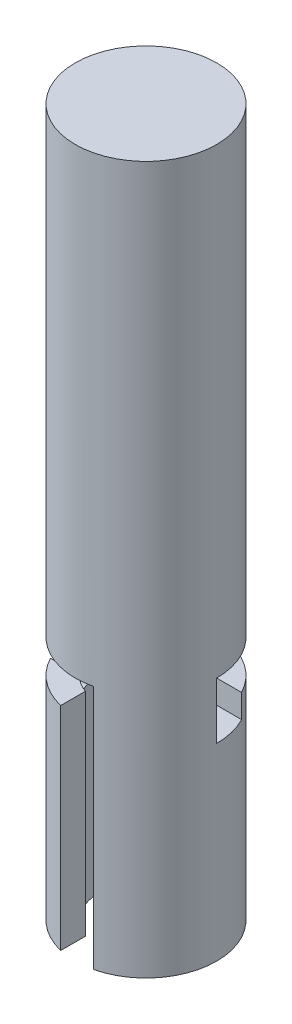
SolidWorks part; units mm, degrees
ref_plane "Front Plane" through (0, 0, 0) normal (0, 0, 1) x (1, 0, 0)
ref_plane "Top Plane" through (0, 0, 0) normal (0, 1, 0) x (1, 0, 0)
ref_plane "Right Plane" through (0, 0, 0) normal (1, 0, 0) x (0, 0, -1)
sketch "Sketch1" plane through (0, 0, 0) normal (0, 1, 0) x (1, 0, 0)
  circle A0 centre (0, 0) radius 15
  dimension "D1" = 30
extrude "Boss-Extrude1" add sketch "Sketch1" along normal mid plane 150
sketch "Sketch2" plane through (0, -75, 0) normal (0, -1, 0) x (1, 0, 0)
  line L0 (0, 15) -> (0, -15) construction
  line L1 (3.5, 15) -> (3.5, -15)
  line L2 (-3.5, 15) -> (-3.5, -15)
  circle A0 centre (0, 0) radius 15 construction
  arc A1 (3.5, 15) -> (-3.5, 15) centre (0, 15) ccw
  arc A2 (-3.5, -15) -> (3.5, -15) centre (0, -15) ccw
  point P6 (0, 0)
  dimension "D1" = 3.5
extrude "Cut-Extrude1" cut sketch "Sketch2" against normal blind 52
ref_plane "Plane1" through (0, -26.5, 0) normal (0, 1, 0) x (1, 0, 0)
sketch "Sketch3" plane through (0, -26.5, 0) normal (0, 1, 0) x (1, 0, 0)
  line L1 (-14.9801, 0) -> (-15.3281, -9.9939)
  line L2 (0, -7) -> (-0.348, -16.9939)
  line L3 (15, 0) -> (0, 7)
  line L4 (15, 0) -> (15.348, 9.9939)
  line L5 (0, 7) -> (0.348, 16.9939)
  line L6 (15.348, 9.9939) -> (0.348, 16.9939)
  line L7 (-15.3281, -9.9939) -> (-0.348, -16.9939)
  line L8 (-14.9801, 0) -> (0, -7)
  circle A0 centre (0, 0) radius 15 construction
  point P0 (0, -7)
  point P5 (-14.9801, 0)
  dimension "D1" = 7
  dimension "D2" = 7
  dimension "D3" = 10
extrude "Cut-Extrude2" cut sketch "Sketch3" against normal mid plane 7
ref_plane "Plane2" through (0, -35, 0) normal (0, 1, 0) x (1, 0, 0)
sketch "Sketch9" plane through (0, -75, 0) normal (0, -1, 0) x (1, 0, 0)
  circle A0 centre (0, 0) radius 10
  dimension "D1" = 20
extrude "Cut-Extrude12" cut sketch "Sketch9" against normal blind 70
ref_plane "Plane5" through (15, 0, 0) normal (1, 0, 0) x (0, 0, -1)
sketch "Sketch17" plane through (15, 0, 0) normal (1, 0, 0) x (0, 0, -1)
  line L0 (0, -23) -> (0, -35)
  line L1 (0, -23) -> (7, -23)
  line L2 (0, -35) -> (7, -35)
  line L3 (7, -23) -> (7, -35)
  line L4 (16.5, -35) -> (-16.5, -35) construction
  dimension "D1" = 7
extrude "Cut-Extrude19" cut sketch "Sketch17" against normal blind 15
ref_plane "Plane6" through (-15, 0, 0) normal (1, 0, 0) x (0, 0, -1)
ref_plane "Plane7" through (-15, 0, 0) normal (-1, 0, 0) x (0, 0, 1)
sketch "Sketch19" plane through (-15, 0, 0) normal (-1, 0, 0) x (0, 0, 1)
  line L0 (0, -23) -> (0, -35)
  line L1 (0, -23) -> (7, -23)
  line L2 (0, -35) -> (7, -35)
  line L3 (7, -23) -> (7, -35)
  line L4 (2.4722, -23) -> (0, -23) construction
  line L5 (16.5, -35) -> (-16.5, -35) construction
  dimension "D1" = 7
extrude "Cut-Extrude20" cut sketch "Sketch19" against normal blind 15
